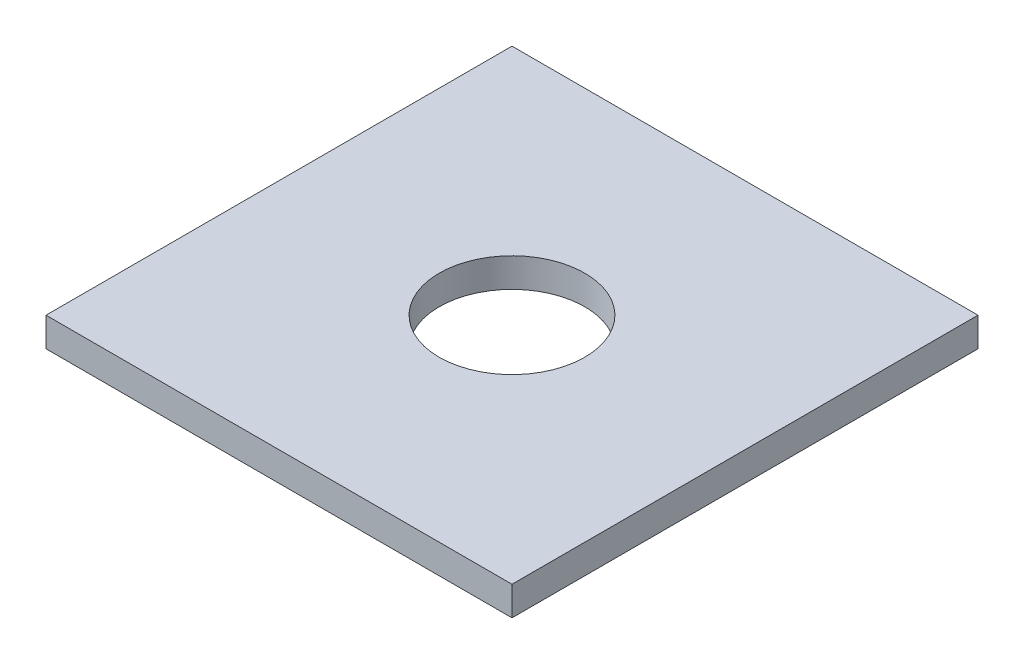
SolidWorks part; units mm, degrees
ref_plane "前视基准面" through (0, 0, 0) normal (0, 0, 1) x (1, 0, 0)
ref_plane "上视基准面" through (0, 0, 0) normal (0, 1, 0) x (1, 0, 0)
ref_plane "右视基准面" through (0, 0, 0) normal (1, 0, 0) x (0, 0, -1)
sketch "草图1" plane through (0, 0, 0) normal (0, 1, 0) x (1, 0, 0)
  line L1 (-8, 8) -> (8, 8)
  line L2 (-8, 8) -> (-8, -8)
  line L3 (-8, -8) -> (8, -8)
  line L4 (8, 8) -> (8, -8)
  line L5 (-8, 8) -> (8, -8) construction
  line L6 (-8, -8) -> (8, 8) construction
  point P0 (0, 0)
  dimension "D1" = 16
  dimension "D2" = 16
extrude "凸台-拉伸1" add sketch "草图1" along normal blind 1
sketch "草图2" plane through (0, 1, 0) normal (0, 1, 0) x (1, 0, 0)
  circle A0 centre (0, 0) radius 2.5
  dimension "D1" = 5
extrude "切除-拉伸1" cut sketch "草图2" against normal blind 1
